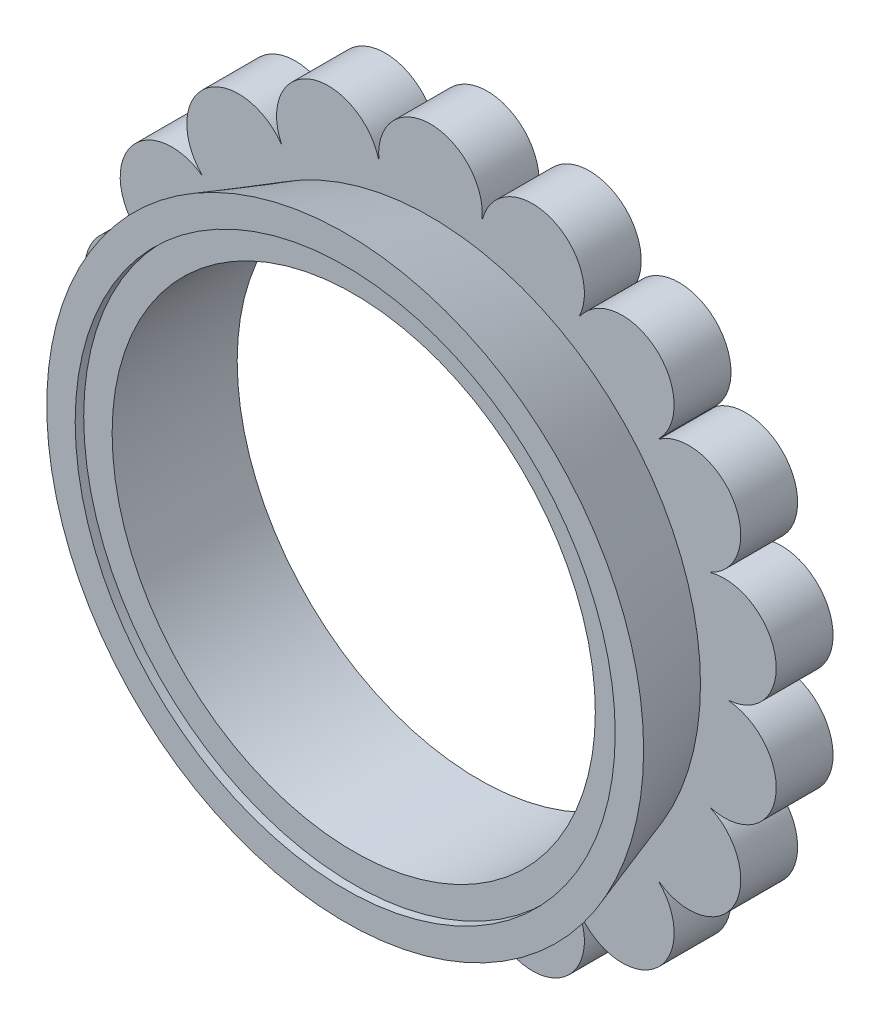
SolidWorks part; units mm, degrees
ref_plane "前视基准面" through (0, 0, 0) normal (0, 0, 1) x (1, 0, 0)
ref_plane "上视基准面" through (0, 0, 0) normal (0, 1, 0) x (1, 0, 0)
ref_plane "右视基准面" through (0, 0, 0) normal (1, 0, 0) x (0, 0, -1)
sketch "草图1" plane through (0, 0, 0) normal (1, 0, 0) x (0, 0, -1)
  line L0 (0, 0) -> (8.1838, 0) construction
  line L1 (0, 8.5) -> (0, 10.5)
  line L2 (0, 10.5) -> (3, 9.5)
  line L3 (3, 9.5) -> (3, 13.5)
  line L4 (3, 13.5) -> (5, 13.5)
  line L5 (5, 13.5) -> (5, 8.5)
  line L6 (5, 8.5) -> (0, 8.5)
  dimension "D1" = 3
  dimension "D2" = 2
  dimension "D3" = 1
  dimension "D4" = 2
  dimension "D5" = 8.5
  dimension "D6" = 5
revolve "旋转1" add sketch "草图1" angle 360 about L0
sketch "草图2" plane through (0, 0, -3) normal (0, 0, 1) x (1, 0, 0)
  line L0 (0, 14.9064) -> (0, 0) construction
  line L1 (0, 0) -> (2.8899, 16.3892) construction
  circle A0 centre (0, 0) radius 10.5
  circle A1 centre (0, 10.5) radius 1.8233
  circle A2 centre (3.5912, 9.8668) radius 1.8233
  circle A3 centre (6.7493, 8.0435) radius 1.8233
  circle A4 centre (9.0933, 5.25) radius 1.8233
  circle A5 centre (10.3405, 1.8233) radius 1.8233
  circle A6 centre (10.3405, -1.8233) radius 1.8233
  circle A7 centre (9.0933, -5.25) radius 1.8233
  circle A8 centre (6.7493, -8.0435) radius 1.8233
  circle A9 centre (3.5912, -9.8668) radius 1.8233
  circle A10 centre (0, -10.5) radius 1.8233
  circle A11 centre (-3.5912, -9.8668) radius 1.8233
  circle A12 centre (-6.7493, -8.0435) radius 1.8233
  circle A13 centre (-9.0933, -5.25) radius 1.8233
  circle A14 centre (-10.3405, -1.8233) radius 1.8233
  circle A15 centre (-10.3405, 1.8233) radius 1.8233
  circle A16 centre (-9.0933, 5.25) radius 1.8233
  circle A17 centre (-6.7493, 8.0435) radius 1.8233
  circle A18 centre (-3.5912, 9.8668) radius 1.8233
  circle A19 centre (0, 0) radius 13.5
  point P43 (0, 0)
  dimension "D1" = 10
  dimension "D2" = 18
extrude "切除-拉伸3" cut sketch "草图2" against normal up to surface (2 mm away) contours A4 A18 A0 A1 A2 A3 A5 A6 A7 A8 A9 A10 A11 A12 A13 A14 A15 A16 A17
sketch "草图3" plane through (0, 0, 0) normal (0, 0, 1) x (1, 0, 0)
  circle A0 centre (0, 0) radius 9.5
extrude "切除-拉伸4" cut sketch "草图3" against normal blind 0.3
sketch "草图4" plane through (0, 0, -5) normal (0, 0, -1) x (-1, 0, 0)
  circle A0 centre (0, 0) radius 9.5
extrude "切除-拉伸5" cut sketch "草图4" against normal blind 0.3
